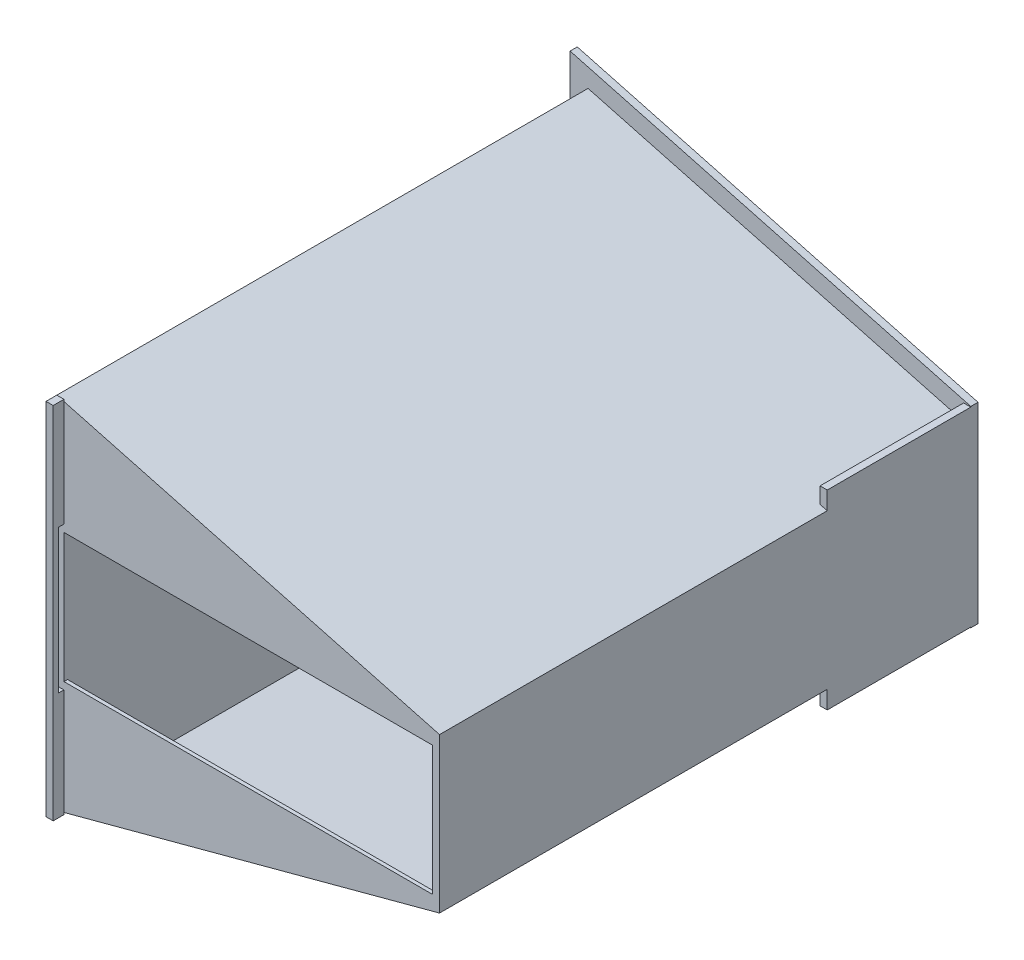
SolidWorks part; units mm, degrees
ref_plane "Front Plane" through (0, 0, 0) normal (0, 0, 1) x (1, 0, 0)
ref_plane "Top Plane" through (0, 0, 0) normal (0, 1, 0) x (1, 0, 0)
ref_plane "Right Plane" through (0, 0, 0) normal (1, 0, 0) x (0, 0, -1)
sketch "Sketch1" plane through (0, 0, 0) normal (0, 0, 1) x (1, 0, 0)
  line L0 (0, 95) -> (0, 0)
  line L1 (0, 0) -> (102.63, 27.5)
  line L2 (102.63, 27.5) -> (102.63, 67.5)
  line L3 (102.63, 67.5) -> (0, 95)
  line L4 (0, 47.5) -> (103.6749, 47.5) construction
  line L5 (-2, 97.6065) -> (-2, -2.6065)
  line L6 (-2, -2.6065) -> (104.63, 25.9654)
  line L7 (104.63, 25.9654) -> (104.63, 69.0346)
  line L8 (104.63, 69.0346) -> (-2, 97.6065)
  line L9 (0, 45.5) -> (103.6749, 45.5) construction
  point P8 (102.63, 47.5)
  dimension "D1" = 102.63
  dimension "D2" = 95
  dimension "D3" = 40
  dimension "D4" = 2
extrude "Boss-Extrude1" add sketch "Sketch1" along normal blind 150 contours L7 L8 L5 L6 L3 L2 L1 L0
sketch "Sketch2" plane through (0, 0, 150) normal (0, 0, 1) x (1, 0, 0)
  line L0 (3, 94.1961) -> (3, 89.1961)
  line L1 (102.63, 67.5) -> (0, 95) construction
  line L2 (3, 89.1961) -> (5, 89.1961)
  line L3 (5, 89.1961) -> (5, 93.6602)
  line L4 (5, 93.6602) -> (3, 94.1961)
  line L5 (0, 95) -> (0, 0) construction
  line L6 (0, 47.5) -> (90.911, 47.5) construction
  line L7 (5, 1.3398) -> (3, 0.8039)
  line L8 (5, 5.8039) -> (5, 1.3398)
  line L9 (3, 5.8039) -> (5, 5.8039)
  line L10 (3, 0.8039) -> (3, 5.8039)
  dimension "D1" = 5
  dimension "D2" = 2
  dimension "D3" = 3
extrude "Boss-Extrude2" [suppressed] add sketch "Sketch2" against normal blind 150 separate body
sketch "Sketch3" plane through (0, 0, 150) normal (0, 0, 1) x (1, 0, 0)
  line L0 (102.63, 65.5) -> (0, 65.5)
  line L1 (102.63, 27.5) -> (102.63, 67.5) construction
  line L2 (0, 95) -> (0, 0) construction
  line L3 (0, 65.5) -> (0, 29.5)
  line L4 (0, 29.5) -> (102.63, 29.5)
  line L6 (0, 65.5) -> (0, 95)
  line L7 (0, 95) -> (102.63, 67.5)
  line L8 (102.63, 67.5) -> (102.63, 65.5)
  line L9 (0, 29.5) -> (0, 0)
  line L10 (0, 0) -> (102.63, 27.5)
  line L11 (102.63, 27.5) -> (102.63, 29.5)
  line M9 (0, 95) -> (102.63, 67.5)
  line M10 (102.63, 67.5) -> (102.63, 27.5)
  line M11 (102.63, 27.5) -> (0, 0)
  line M12 (0, 0) -> (0, 95)
  dimension "D1" = 2
  dimension "D2" = 2
extrude "Boss-Extrude3" add sketch "Sketch3" against normal blind 1 separate body contours L0 M10 M9 M12 | L4 M12 M11 M10
ref_plane "Plane1" through (0, 0, 148) normal (0, 0, -1) x (-1, 0, 0)
sketch "Sketch4" plane through (0, 0, 148) normal (0, 0, -1) x (-1, 0, 0)
  line L0 (-102.63, 65.5) -> (0, 65.5) construction
  line L1 (0, 65.5) -> (0, 95) construction
  line L2 (0, 95) -> (-102.63, 67.5) construction
  line L3 (-102.63, 67.5) -> (-102.63, 65.5) construction
  line L4 (0, 29.5) -> (-102.63, 29.5) construction
  line L5 (-102.63, 29.5) -> (-102.63, 27.5) construction
  line L6 (-102.63, 27.5) -> (0, 0) construction
  line L7 (0, 0) -> (0, 29.5) construction
  line L8 (-102.63, 65.5) -> (0, 65.5)
  line L9 (0, 65.5) -> (0, 95)
  line L10 (0, 95) -> (-102.63, 67.5)
  line L11 (-102.63, 67.5) -> (-102.63, 65.5)
  line L12 (0, 29.5) -> (-102.63, 29.5)
  line L13 (-102.63, 29.5) -> (-102.63, 27.5)
  line L14 (-102.63, 27.5) -> (0, 0)
  line L15 (0, 0) -> (0, 29.5)
extrude "Boss-Extrude4" [suppressed] add sketch "Sketch4" along normal blind 1
sketch "Sketch6" plane through (-2, 0, 0) normal (-1, 0, 0) x (0, 0, 1)
  line L6 (150, 67.5) -> (151.5, 67.5)
  line L9 (151.5, 67.5) -> (151.5, 27.5)
  line L14 (151.5, 27.5) -> (150, 27.5)
  line L15 (150, -2.6065) -> (153, -2.6065)
  line L16 (153, -2.6065) -> (153, 97.6065)
  line L17 (153, 97.6065) -> (150, 97.6065)
  line L18 (150, 97.6065) -> (150, 67.5)
  line L19 (150, 27.5) -> (150, -2.6065)
  line L20 (150, 97.6065) -> (0, 97.6065) construction
  line L21 (150, 97.6065) -> (150, -2.6065) construction
  dimension "D1" = 3
  dimension "D2" = 1.5
extrude "Boss-Extrude5" add sketch "Sketch6" against normal blind 2
sketch "Sketch7" plane through (0, 0, 0) normal (0, 0, -1) x (-1, 0, 0)
  line L1 (-104.63, 20.789) -> (7, -9.1226)
  line L2 (7, -9.1226) -> (7, 104.1226)
  line L3 (7, 104.1226) -> (-104.63, 74.211)
  line L4 (-104.63, 69.0346) -> (-104.63, 25.9654)
  line L5 (-104.63, 25.9654) -> (2, -2.6065)
  line L6 (2, -2.6065) -> (2, 97.6065)
  line L7 (2, 97.6065) -> (-104.63, 69.0346)
  line L8 (-104.63, 74.211) -> (-104.63, 69.0346)
  line L9 (-104.63, 25.9654) -> (2, -2.6065)
  line L10 (2, -2.6065) -> (2, 97.6065)
  line L11 (2, 97.6065) -> (-104.63, 69.0346)
  line L12 (-104.63, 69.0346) -> (-104.63, 25.9654) construction
  line L13 (-104.63, 25.9654) -> (-104.63, 20.789)
  line L14 (7, 104.1226) -> (-109.63, 72.8713) construction
  line L15 (-109.63, 22.1287) -> (7, -9.1226) construction
  line L16 (-109.63, 72.8713) -> (-109.63, 22.1287) construction
  dimension "D1" = 0
  dimension "D2" = 5
extrude "Boss-Extrude6" add sketch "Sketch7" against normal blind 2
sketch "Sketch8" plane through (104.63, 0, 0) normal (1, 0, 0) x (0, 0, -1)
  line L0 (-2, 69.0346) -> (-42, 69.0346)
  line L1 (-150, 69.0346) -> (-2, 69.0346) construction
  line L2 (-42, 69.0346) -> (-42, 74.0346)
  line L4 (-42, 74.0346) -> (-2, 74.0346)
  line L5 (-2, 97.6065) -> (-2, 69.0346) construction
  line L6 (-2, 74.0346) -> (-2, 69.0346)
  line L7 (0, 47.5) -> (-84.6391, 47.5) construction
  line L9 (-2, 20.9654) -> (-2, 25.9654)
  line L10 (-42, 20.9654) -> (-2, 20.9654)
  line L11 (-42, 25.9654) -> (-42, 20.9654)
  line L12 (-2, 25.9654) -> (-42, 25.9654)
  line L13 (0, 20.789) -> (0, 74.211) construction
  dimension "D1" = 40
  dimension "D2" = 5
extrude "Boss-Extrude7" add sketch "Sketch8" against normal blind 2
